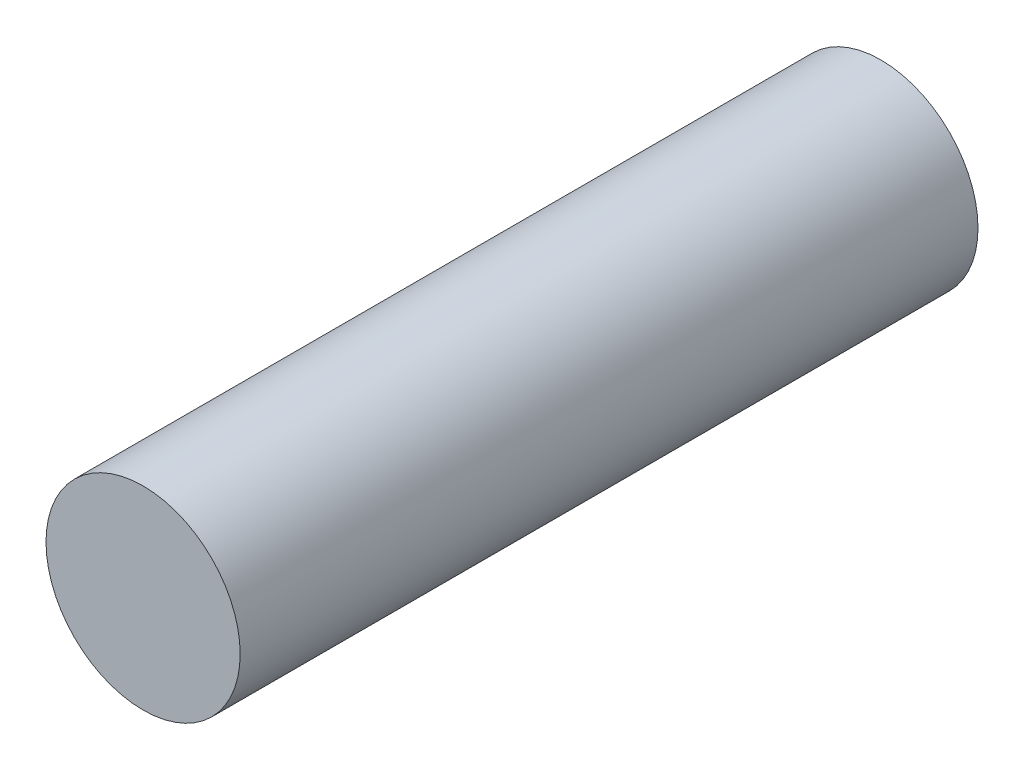
SolidWorks part; units mm, degrees
ref_plane "Front Plane" through (0, 0, 0) normal (0, 0, 1) x (1, 0, 0)
ref_plane "Top Plane" through (0, 0, 0) normal (0, 1, 0) x (1, 0, 0)
ref_plane "Right Plane" through (0, 0, 0) normal (1, 0, 0) x (0, 0, -1)
sketch "Sketch1" plane through (0, 0, 0) normal (0, 0, 1) x (1, 0, 0)
  circle A0 centre (0, 0) radius 1.075
  dimension "D1" = 2.15
extrude "Boss-Extrude1" add sketch "Sketch1" along normal blind 8.17
